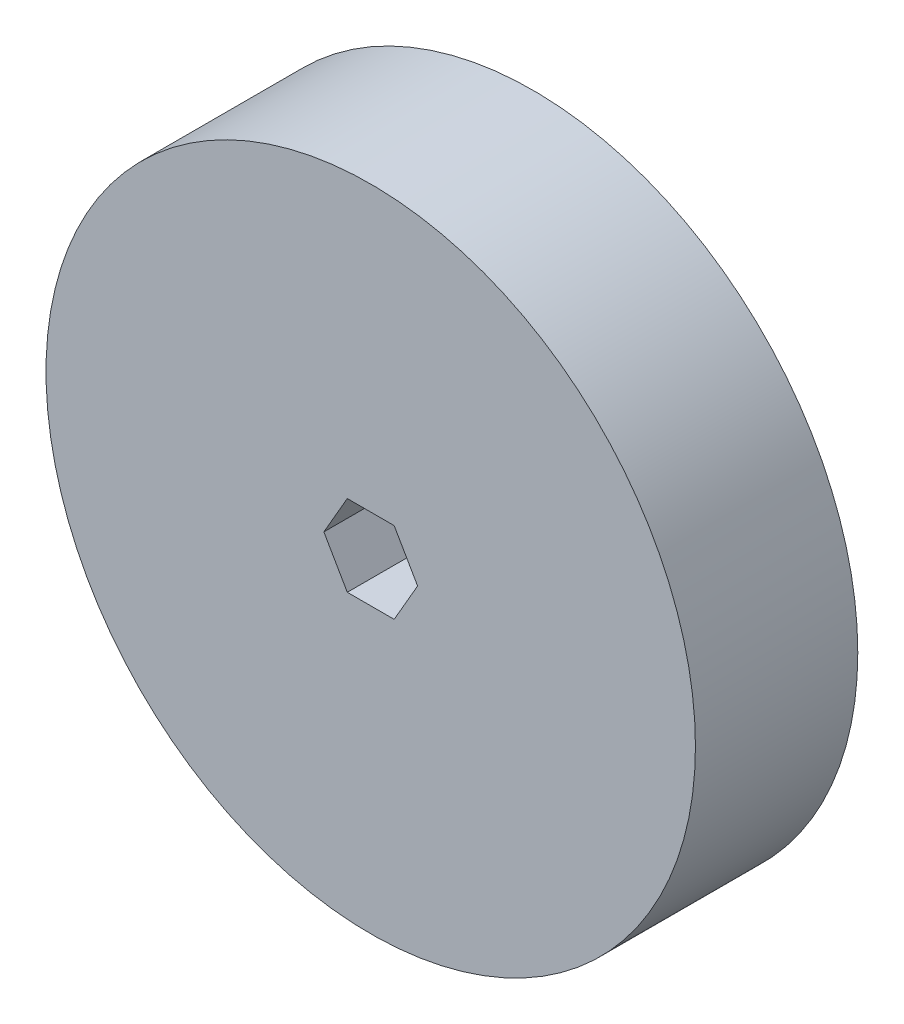
SolidWorks part; units mm, degrees
ref_plane "Front Plane" through (0, 0, 0) normal (0, 0, 1) x (1, 0, 0)
ref_plane "Top Plane" through (0, 0, 0) normal (0, 1, 0) x (1, 0, 0)
ref_plane "Right Plane" through (0, 0, 0) normal (1, 0, 0) x (0, 0, -1)
sketch "Sketch1" plane through (0, 0, 0) normal (0, 0, 1) x (1, 0, 0)
  line L1 (7.3323, 0) -> (3.6662, 6.35)
  line L2 (3.6662, 6.35) -> (-3.6662, 6.35)
  line L3 (-3.6662, 6.35) -> (-7.3323, 0)
  line L4 (-7.3323, 0) -> (-3.6662, -6.35)
  line L5 (-3.6662, -6.35) -> (3.6662, -6.35)
  line L6 (3.6662, -6.35) -> (7.3323, 0)
  circle A0 centre (0, 0) radius 50.8
  circle A1 centre (0, 0) radius 6.35 construction
  dimension "D1" = 12.7
  dimension "D2" = 101.6
extrude "Boss-Extrude1" add sketch "Sketch1" along normal blind 25.4
